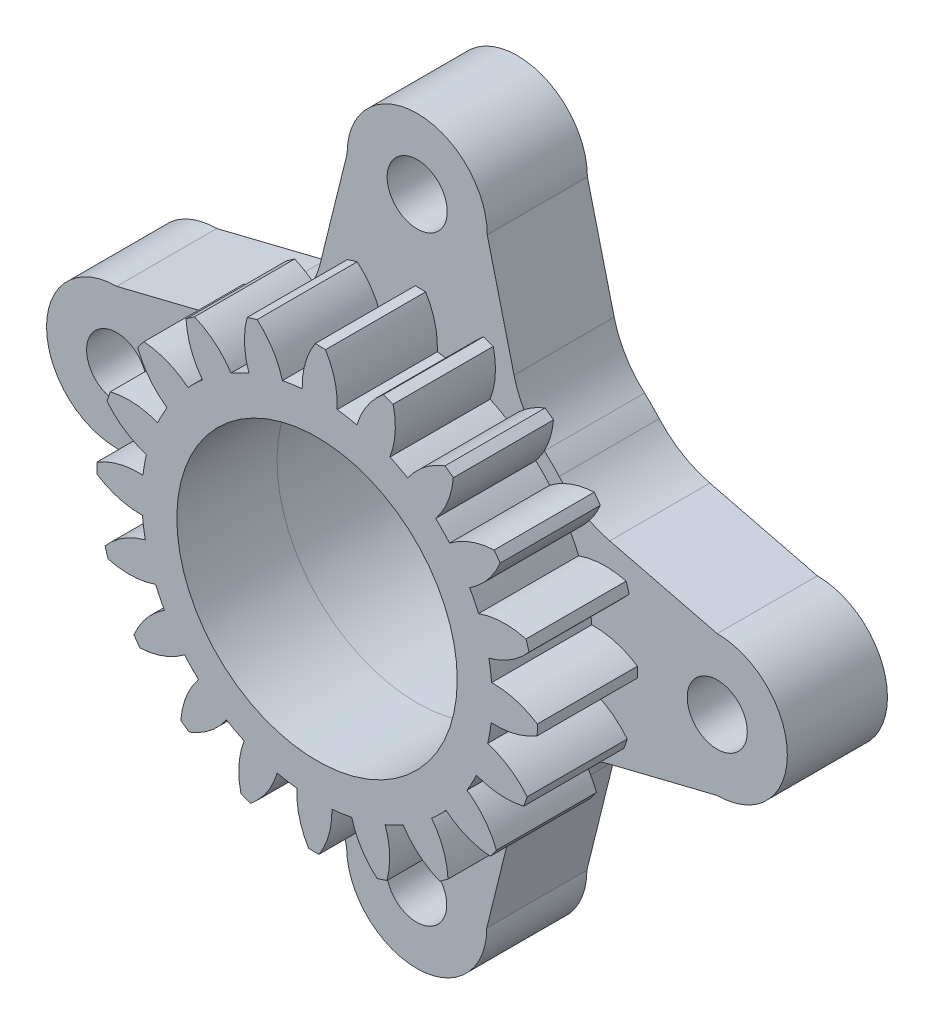
SolidWorks part; units mm, degrees
ref_plane "Front Plane" through (0, 0, 0) normal (0, 0, 1) x (1, 0, 0)
ref_plane "Top Plane" through (0, 0, 0) normal (0, 1, 0) x (1, 0, 0)
ref_plane "Right Plane" through (0, 0, 0) normal (1, 0, 0) x (0, 0, -1)
sketch "Sketch1" plane through (0, 0, 0) normal (0, 0, 1) x (1, 0, 0)
  line L1 (-3.487, 14.9951) -> (-4.8233, 9.5955)
  line L5 (3.5119, 14.9951) -> (4.8483, 9.5956)
  line L7 (14.9951, -3.5119) -> (9.6082, -4.8452)
  line L8 (14.9951, 3.487) -> (9.6269, 4.8155)
  line L9 (-3.5119, -14.9951) -> (-4.8527, -9.5778)
  line L10 (3.487, -14.9951) -> (4.8132, -9.6361)
  line L11 (-14.9951, 3.5119) -> (-9.5652, 4.8558)
  line L12 (-14.9951, -3.487) -> (-9.6046, -4.821)
  line L13 (-2.1052, -6.6768) -> (-1.6771, -6.7827)
  line L15 (2.0906, 6.6804) -> (1.6771, 6.7827)
  line L17 (6.6352, -2.2733) -> (6.7827, -1.6771)
  circle A1 centre (0.0127, -0.0045) radius 7.0004
  circle A3 centre (0.0124, 14.9951) radius 1.5
  arc A4 (3.5119, 14.9951) -> (-3.487, 14.9951) centre (0.0124, 14.9951) ccw
  arc A10 (-7.0779, -6.3424) -> (-6.3573, -7.0663) centre (0.0127, -0.0045) ccw
  circle A11 centre (14.9951, -0.0124) radius 1.5
  arc A12 (14.9951, -3.5119) -> (14.9951, 3.487) centre (14.9951, -0.0124) ccw
  circle A13 centre (-0.0124, -14.9951) radius 1.5
  arc A14 (-3.5119, -14.9951) -> (3.487, -14.9951) centre (-0.0124, -14.9951) ccw
  circle A15 centre (-14.9951, 0.0124) radius 1.5
  arc A16 (-14.9951, 3.5119) -> (-14.9951, -3.487) centre (-14.9951, 0.0124) ccw
  arc A17 (-6.338, 7.0747) -> (-7.0522, 6.3621) centre (0.0127, -0.0045) ccw
  arc A18 (7.1012, 6.3357) -> (6.3631, 7.0749) centre (0.0127, -0.0045) ccw
  arc A19 (6.3402, -7.1044) -> (7.0891, -6.3582) centre (0.0127, -0.0045) ccw
  arc A20 (4.8483, 9.5956) -> (6.3631, 7.0749) centre (9.7018, 10.7969) ccw
  arc A21 (7.1012, 6.3357) -> (9.6269, 4.8155) centre (10.828, 9.6691) ccw
  arc A22 (9.6082, -4.8452) -> (7.0891, -6.3582) centre (10.8095, -9.6987) ccw
  arc A23 (6.3402, -7.1044) -> (4.8132, -9.6361) centre (9.6668, -10.8371) ccw
  arc A24 (-4.8527, -9.5778) -> (-6.3573, -7.0663) centre (-9.7062, -10.779) ccw
  arc A25 (-7.0779, -6.3424) -> (-9.6046, -4.821) centre (-10.8057, -9.6746) ccw
  arc A26 (-7.0522, 6.3621) -> (-9.5652, 4.8558) centre (-10.7665, 9.7093) cw
  arc A27 (-6.338, 7.0747) -> (-4.8233, 9.5955) centre (-9.6768, 10.7965) ccw
  point P28 (0, 0)
  point P31 (0, 0)
  point P38 (7.953, 5.2297)
  point P43 (5.2288, -7.9567)
  point P52 (-5.2364, 7.9261)
  dimension "D1" = 4
  dimension "D2" = 5
extrude "Boss-Extrude1" add sketch "Sketch1" along normal blind 5 contours A27 A17 A26 L11 A16 L12 A25 A10 A24 L9 A14 L10 A23 A19 A22 L7 A12 L8 A21 A18 A20 L5 A4 L1 A15 A13 A11 A3 A1
sketch "Sketch2" plane through (0, 0, 5) normal (0, 0, 1) x (1, 0, 0)
  circle A0 centre (0.0124, -0.0047) radius 7.0001 construction
  circle A1 centre (0.0124, -0.0047) radius 7.0001
  arc A80 (-1.9756, -8.5245) -> (-0.9906, -8.6957) centre (0.0128, -0.0044) ccw
  arc A81 (-0.9906, -8.6957) -> (-0.411, -10.9963) centre (3.0035, -8.9127) ccw
  arc A82 (-0.411, -10.9963) -> (0.106, -11.004) centre (0.0128, -0.0044) ccw
  arc A83 (0.106, -11.004) -> (0.7545, -8.7219) centre (-3.2443, -8.8188) ccw
  arc A84 (0.7545, -8.7219) -> (1.7443, -8.5804) centre (0.0128, -0.0044) ccw
  arc A85 (1.7443, -8.5804) -> (3.0064, -10.5893) centre (5.61, -7.5526) ccw
  arc A86 (3.0064, -10.5893) -> (3.5005, -10.4369) centre (0.0128, -0.0044) ccw
  arc A87 (3.5005, -10.4369) -> (3.4121, -8.0661) centre (-0.3611, -9.3939) ccw
  arc A88 (3.4121, -8.0661) -> (4.3097, -7.6256) centre (0.0128, -0.0044) ccw
  arc A89 (4.3097, -7.6256) -> (6.1308, -9.1461) centre (7.6685, -5.4535) ccw
  arc A90 (6.1308, -9.1461) -> (6.5536, -8.8485) centre (0.0128, -0.0044) ccw
  arc A91 (6.5536, -8.8485) -> (5.7369, -6.6211) centre (2.5587, -9.0499) ccw
  arc A92 (5.7369, -6.6211) -> (6.4544, -5.9248) centre (0.0128, -0.0044) ccw
  arc A93 (6.4544, -5.9248) -> (8.6563, -6.8081) centre (8.9777, -2.8211) ccw
  arc A94 (8.6563, -6.8081) -> (8.9665, -6.3944) centre (0.0128, -0.0044) ccw
  arc A95 (8.9665, -6.3944) -> (7.5014, -4.5284) centre (5.2293, -7.8205) ccw
  arc A96 (7.5014, -4.5284) -> (7.9686, -3.6445) centre (0.0128, -0.0044) ccw
  arc A97 (7.9686, -3.6445) -> (10.3357, -3.8042) centre (9.4093, 0.0871) ccw
  arc A98 (10.3357, -3.8042) -> (10.5029, -3.3149) centre (0.0128, -0.0044) ccw
  arc A99 (10.5029, -3.3149) -> (8.5329, -1.9929) centre (7.3893, -5.826) ccw
  arc A100 (8.5329, -1.9929) -> (8.7041, -1.0078) centre (0.0128, -0.0044) ccw
  arc A101 (8.7041, -1.0078) -> (11.0047, -0.4282) centre (8.9211, 2.9863) ccw
  arc A102 (11.0047, -0.4282) -> (11.0124, 0.0888) centre (0.0128, -0.0044) ccw
  arc A103 (11.0124, 0.0888) -> (8.7303, 0.7372) centre (8.8272, -3.2616) ccw
  arc A104 (8.7303, 0.7372) -> (8.5888, 1.727) centre (0.0128, -0.0044) ccw
  arc A105 (8.5888, 1.727) -> (10.5976, 2.9892) centre (7.5609, 5.5927) ccw
  arc A106 (10.5976, 2.9892) -> (10.4453, 3.4833) centre (0.0128, -0.0044) ccw
  arc A107 (10.4453, 3.4833) -> (8.0745, 3.3948) centre (9.4023, -0.3784) ccw
  arc A108 (8.0745, 3.3948) -> (7.634, 4.2924) centre (0.0128, -0.0044) ccw
  arc A109 (7.634, 4.2924) -> (9.1545, 6.1135) centre (5.4619, 7.6513) ccw
  arc A110 (9.1545, 6.1135) -> (8.8569, 6.5364) centre (0.0128, -0.0044) ccw
  arc A111 (8.8569, 6.5364) -> (6.6295, 5.7196) centre (9.0583, 2.5414) ccw
  arc A112 (6.6295, 5.7196) -> (5.9332, 6.4372) centre (0.0128, -0.0044) ccw
  arc A113 (5.9332, 6.4372) -> (6.8165, 8.639) centre (2.8295, 8.9604) ccw
  arc A114 (6.8165, 8.639) -> (6.4028, 8.9492) centre (0.0128, -0.0044) ccw
  arc A115 (6.4028, 8.9492) -> (4.5368, 7.4841) centre (7.8289, 5.212) ccw
  arc A116 (4.5368, 7.4841) -> (3.6529, 7.9514) centre (0.0128, -0.0044) ccw
  arc A117 (3.6529, 7.9514) -> (3.8126, 10.3185) centre (-0.0787, 9.392) ccw
  arc A118 (3.8126, 10.3185) -> (3.3233, 10.4856) centre (0.0128, -0.0044) ccw
  arc A119 (3.3233, 10.4856) -> (2.0013, 8.5156) centre (5.8343, 7.372) ccw
  arc A120 (2.0013, 8.5156) -> (1.0162, 8.6868) centre (0.0128, -0.0044) ccw
  arc A121 (1.0162, 8.6868) -> (0.4366, 10.9874) centre (-2.9779, 8.9039) ccw
  arc A122 (0.4366, 10.9874) -> (-0.0804, 10.9952) centre (0.0128, -0.0044) ccw
  arc A123 (-0.0804, 10.9952) -> (-0.7289, 8.7131) centre (3.27, 8.8099) ccw
  arc A124 (-0.7289, 8.7131) -> (-1.7186, 8.5715) centre (0.0128, -0.0044) ccw
  arc A125 (-1.7186, 8.5715) -> (-2.9808, 10.5804) centre (-5.5843, 7.5437) ccw
  arc A126 (-2.9808, 10.5804) -> (-3.4749, 10.428) centre (0.0128, -0.0044) ccw
  arc A127 (-3.4749, 10.428) -> (-3.3864, 8.0572) centre (0.3868, 9.385) ccw
  arc A128 (-3.3864, 8.0572) -> (-4.284, 7.6167) centre (0.0128, -0.0044) ccw
  arc A129 (-4.284, 7.6167) -> (-6.1051, 9.1372) centre (-7.6429, 5.4446) ccw
  arc A130 (-6.1051, 9.1372) -> (-6.528, 8.8396) centre (0.0128, -0.0044) ccw
  arc A131 (-6.528, 8.8396) -> (-5.7112, 6.6122) centre (-2.5331, 9.041) ccw
  arc A132 (-5.7112, 6.6122) -> (-6.4288, 5.9159) centre (0.0128, -0.0044) ccw
  arc A133 (-6.4288, 5.9159) -> (-8.6306, 6.7993) centre (-8.952, 2.8122) ccw
  arc A134 (-8.6306, 6.7993) -> (-8.9408, 6.3856) centre (0.0128, -0.0044) ccw
  arc A135 (-8.9408, 6.3856) -> (-7.4757, 4.5195) centre (-5.2037, 7.8116) ccw
  arc A136 (-7.4757, 4.5195) -> (-7.943, 3.6356) centre (0.0128, -0.0044) ccw
  arc A137 (-7.943, 3.6356) -> (-10.3101, 3.7953) centre (-9.3837, -0.096) ccw
  arc A138 (-10.3101, 3.7953) -> (-10.4772, 3.306) centre (0.0128, -0.0044) ccw
  arc A139 (-10.4772, 3.306) -> (-8.5072, 1.984) centre (-7.3636, 5.8171) ccw
  arc A140 (-8.5072, 1.984) -> (-8.6784, 0.999) centre (0.0128, -0.0044) ccw
  arc A141 (-8.6784, 0.999) -> (-10.979, 0.4194) centre (-8.8955, -2.9951) ccw
  arc A142 (-10.979, 0.4194) -> (-10.9868, -0.0976) centre (0.0128, -0.0044) ccw
  arc A143 (-10.9868, -0.0976) -> (-8.7047, -0.7461) centre (-8.8016, 3.2527) ccw
  arc A144 (-8.7047, -0.7461) -> (-8.5631, -1.7359) centre (0.0128, -0.0044) ccw
  arc A145 (-8.5631, -1.7359) -> (-10.572, -2.998) centre (-7.5353, -5.6016) ccw
  arc A146 (-10.572, -2.998) -> (-10.4196, -3.4921) centre (0.0128, -0.0044) ccw
  arc A147 (-10.4196, -3.4921) -> (-8.0488, -3.4037) centre (-9.3767, 0.3695) ccw
  arc A148 (-8.0488, -3.4037) -> (-7.6083, -4.3013) centre (0.0128, -0.0044) ccw
  arc A149 (-7.6083, -4.3013) -> (-9.1289, -6.1224) centre (-5.4362, -7.6601) ccw
  arc A150 (-9.1289, -6.1224) -> (-8.8313, -6.5452) centre (0.0128, -0.0044) ccw
  arc A151 (-8.8313, -6.5452) -> (-6.6038, -5.7285) centre (-9.0327, -2.5503) ccw
  arc A152 (-6.6038, -5.7285) -> (-5.9075, -6.446) centre (0.0128, -0.0044) ccw
  arc A153 (-5.9075, -6.446) -> (-6.7909, -8.6479) centre (-2.8038, -8.9693) ccw
  arc A154 (-6.7909, -8.6479) -> (-6.3772, -8.9581) centre (0.0128, -0.0044) ccw
  arc A155 (-6.3772, -8.9581) -> (-4.5112, -7.493) centre (-7.8032, -5.2209) ccw
  arc A156 (-4.5112, -7.493) -> (-3.6272, -7.9603) centre (0.0128, -0.0044) ccw
  arc A157 (-3.6272, -7.9603) -> (-3.7869, -10.3273) centre (0.1043, -9.4009) ccw
  arc A158 (-3.7869, -10.3273) -> (-3.2976, -10.4945) centre (0.0128, -0.0044) ccw
  arc A159 (-3.2976, -10.4945) -> (-1.9756, -8.5245) centre (-5.8087, -7.3809) ccw
  arc A160 (-1.9756, -8.5245) -> (-0.9906, -8.6957) centre (0.0128, -0.0044) ccw
  arc A161 (-0.9906, -8.6957) -> (-0.411, -10.9963) centre (3.0035, -8.9127) ccw
  arc A162 (-0.411, -10.9963) -> (0.106, -11.004) centre (0.0128, -0.0044) ccw
  arc A163 (0.106, -11.004) -> (0.7545, -8.7219) centre (-3.2443, -8.8188) ccw
  arc A164 (0.7545, -8.7219) -> (1.7443, -8.5804) centre (0.0128, -0.0044) ccw
  arc A165 (1.7443, -8.5804) -> (3.0064, -10.5893) centre (5.61, -7.5526) ccw
  arc A166 (3.0064, -10.5893) -> (3.5005, -10.4369) centre (0.0128, -0.0044) ccw
  arc A167 (3.5005, -10.4369) -> (3.4121, -8.0661) centre (-0.3611, -9.3939) ccw
  arc A168 (3.4121, -8.0661) -> (4.3097, -7.6256) centre (0.0128, -0.0044) ccw
  arc A169 (4.3097, -7.6256) -> (6.1308, -9.1461) centre (7.6685, -5.4535) ccw
  arc A170 (6.1308, -9.1461) -> (6.5536, -8.8485) centre (0.0128, -0.0044) ccw
  arc A171 (6.5536, -8.8485) -> (5.7369, -6.6211) centre (2.5587, -9.0499) ccw
  arc A172 (5.7369, -6.6211) -> (6.4544, -5.9248) centre (0.0128, -0.0044) ccw
  arc A173 (6.4544, -5.9248) -> (8.6563, -6.8081) centre (8.9777, -2.8211) ccw
  arc A174 (8.6563, -6.8081) -> (8.9665, -6.3944) centre (0.0128, -0.0044) ccw
  arc A175 (8.9665, -6.3944) -> (7.5014, -4.5284) centre (5.2293, -7.8205) ccw
  arc A176 (7.5014, -4.5284) -> (7.9686, -3.6445) centre (0.0128, -0.0044) ccw
  arc A177 (7.9686, -3.6445) -> (10.3357, -3.8042) centre (9.4093, 0.0871) ccw
  arc A178 (10.3357, -3.8042) -> (10.5029, -3.3149) centre (0.0128, -0.0044) ccw
  arc A179 (10.5029, -3.3149) -> (8.5329, -1.9929) centre (7.3893, -5.826) ccw
  arc A180 (8.5329, -1.9929) -> (8.7041, -1.0078) centre (0.0128, -0.0044) ccw
  arc A181 (8.7041, -1.0078) -> (11.0047, -0.4282) centre (8.9211, 2.9863) ccw
  arc A182 (11.0047, -0.4282) -> (11.0124, 0.0888) centre (0.0128, -0.0044) ccw
  arc A183 (11.0124, 0.0888) -> (8.7303, 0.7372) centre (8.8272, -3.2616) ccw
  arc A184 (8.7303, 0.7372) -> (8.5888, 1.727) centre (0.0128, -0.0044) ccw
  arc A185 (8.5888, 1.727) -> (10.5976, 2.9892) centre (7.5609, 5.5927) ccw
  arc A186 (10.5976, 2.9892) -> (10.4453, 3.4833) centre (0.0128, -0.0044) ccw
  arc A187 (10.4453, 3.4833) -> (8.0745, 3.3948) centre (9.4023, -0.3784) ccw
  arc A188 (8.0745, 3.3948) -> (7.634, 4.2924) centre (0.0128, -0.0044) ccw
  arc A189 (7.634, 4.2924) -> (9.1545, 6.1135) centre (5.4619, 7.6513) ccw
  arc A190 (9.1545, 6.1135) -> (8.8569, 6.5364) centre (0.0128, -0.0044) ccw
  arc A191 (8.8569, 6.5364) -> (6.6295, 5.7196) centre (9.0583, 2.5414) ccw
  arc A192 (6.6295, 5.7196) -> (5.9332, 6.4372) centre (0.0128, -0.0044) ccw
  arc A193 (5.9332, 6.4372) -> (6.8165, 8.639) centre (2.8295, 8.9604) ccw
  arc A194 (6.8165, 8.639) -> (6.4028, 8.9492) centre (0.0128, -0.0044) ccw
  arc A195 (6.4028, 8.9492) -> (4.5368, 7.4841) centre (7.8289, 5.212) ccw
  arc A196 (4.5368, 7.4841) -> (3.6529, 7.9514) centre (0.0128, -0.0044) ccw
  arc A197 (3.6529, 7.9514) -> (3.8126, 10.3185) centre (-0.0787, 9.392) ccw
  arc A198 (3.8126, 10.3185) -> (3.3233, 10.4856) centre (0.0128, -0.0044) ccw
  arc A199 (3.3233, 10.4856) -> (2.0013, 8.5156) centre (5.8343, 7.372) ccw
  arc A200 (2.0013, 8.5156) -> (1.0162, 8.6868) centre (0.0128, -0.0044) ccw
  arc A201 (1.0162, 8.6868) -> (0.4366, 10.9874) centre (-2.9779, 8.9039) ccw
  arc A202 (0.4366, 10.9874) -> (-0.0804, 10.9952) centre (0.0128, -0.0044) ccw
  arc A203 (-0.0804, 10.9952) -> (-0.7289, 8.7131) centre (3.27, 8.8099) ccw
  arc A204 (-0.7289, 8.7131) -> (-1.7186, 8.5715) centre (0.0128, -0.0044) ccw
  arc A205 (-1.7186, 8.5715) -> (-2.9808, 10.5804) centre (-5.5843, 7.5437) ccw
  arc A206 (-2.9808, 10.5804) -> (-3.4749, 10.428) centre (0.0128, -0.0044) ccw
  arc A207 (-3.4749, 10.428) -> (-3.3864, 8.0572) centre (0.3868, 9.385) ccw
  arc A208 (-3.3864, 8.0572) -> (-4.284, 7.6167) centre (0.0128, -0.0044) ccw
  arc A209 (-4.284, 7.6167) -> (-6.1051, 9.1372) centre (-7.6429, 5.4446) ccw
  arc A210 (-6.1051, 9.1372) -> (-6.528, 8.8396) centre (0.0128, -0.0044) ccw
  arc A211 (-6.528, 8.8396) -> (-5.7112, 6.6122) centre (-2.5331, 9.041) ccw
  arc A212 (-5.7112, 6.6122) -> (-6.4288, 5.9159) centre (0.0128, -0.0044) ccw
  arc A213 (-6.4288, 5.9159) -> (-8.6306, 6.7993) centre (-8.952, 2.8122) ccw
  arc A214 (-8.6306, 6.7993) -> (-8.9408, 6.3856) centre (0.0128, -0.0044) ccw
  arc A215 (-8.9408, 6.3856) -> (-7.4757, 4.5195) centre (-5.2037, 7.8116) ccw
  arc A216 (-7.4757, 4.5195) -> (-7.943, 3.6356) centre (0.0128, -0.0044) ccw
  arc A217 (-7.943, 3.6356) -> (-10.3101, 3.7953) centre (-9.3837, -0.096) ccw
  arc A218 (-10.3101, 3.7953) -> (-10.4772, 3.306) centre (0.0128, -0.0044) ccw
  arc A219 (-10.4772, 3.306) -> (-8.5072, 1.984) centre (-7.3636, 5.8171) ccw
  arc A220 (-8.5072, 1.984) -> (-8.6784, 0.999) centre (0.0128, -0.0044) ccw
  arc A221 (-8.6784, 0.999) -> (-10.979, 0.4194) centre (-8.8955, -2.9951) ccw
  arc A222 (-10.979, 0.4194) -> (-10.9868, -0.0976) centre (0.0128, -0.0044) ccw
  arc A223 (-10.9868, -0.0976) -> (-8.7047, -0.7461) centre (-8.8016, 3.2527) ccw
  arc A224 (-8.7047, -0.7461) -> (-8.5631, -1.7359) centre (0.0128, -0.0044) ccw
  arc A225 (-8.5631, -1.7359) -> (-10.572, -2.998) centre (-7.5353, -5.6016) ccw
  arc A226 (-10.572, -2.998) -> (-10.4196, -3.4921) centre (0.0128, -0.0044) ccw
  arc A227 (-10.4196, -3.4921) -> (-8.0488, -3.4037) centre (-9.3767, 0.3695) ccw
  arc A228 (-8.0488, -3.4037) -> (-7.6083, -4.3013) centre (0.0128, -0.0044) ccw
  arc A229 (-7.6083, -4.3013) -> (-9.1289, -6.1224) centre (-5.4362, -7.6601) ccw
  arc A230 (-9.1289, -6.1224) -> (-8.8313, -6.5452) centre (0.0128, -0.0044) ccw
  arc A231 (-8.8313, -6.5452) -> (-6.6038, -5.7285) centre (-9.0327, -2.5503) ccw
  arc A232 (-6.6038, -5.7285) -> (-5.9075, -6.446) centre (0.0128, -0.0044) ccw
  arc A233 (-5.9075, -6.446) -> (-6.7909, -8.6479) centre (-2.8038, -8.9693) ccw
  arc A234 (-6.7909, -8.6479) -> (-6.3772, -8.9581) centre (0.0128, -0.0044) ccw
  arc A235 (-6.3772, -8.9581) -> (-4.5112, -7.493) centre (-7.8032, -5.2209) ccw
  arc A236 (-4.5112, -7.493) -> (-3.6272, -7.9603) centre (0.0128, -0.0044) ccw
  arc A237 (-3.6272, -7.9603) -> (-3.7869, -10.3273) centre (0.1043, -9.4009) ccw
  arc A238 (-3.7869, -10.3273) -> (-3.2976, -10.4945) centre (0.0128, -0.0044) ccw
  arc A239 (-3.2976, -10.4945) -> (-1.9756, -8.5245) centre (-5.8087, -7.3809) ccw
  dimension "D1" = 0
extrude "Boss-Extrude2" add sketch "Sketch2" along normal blind 5
